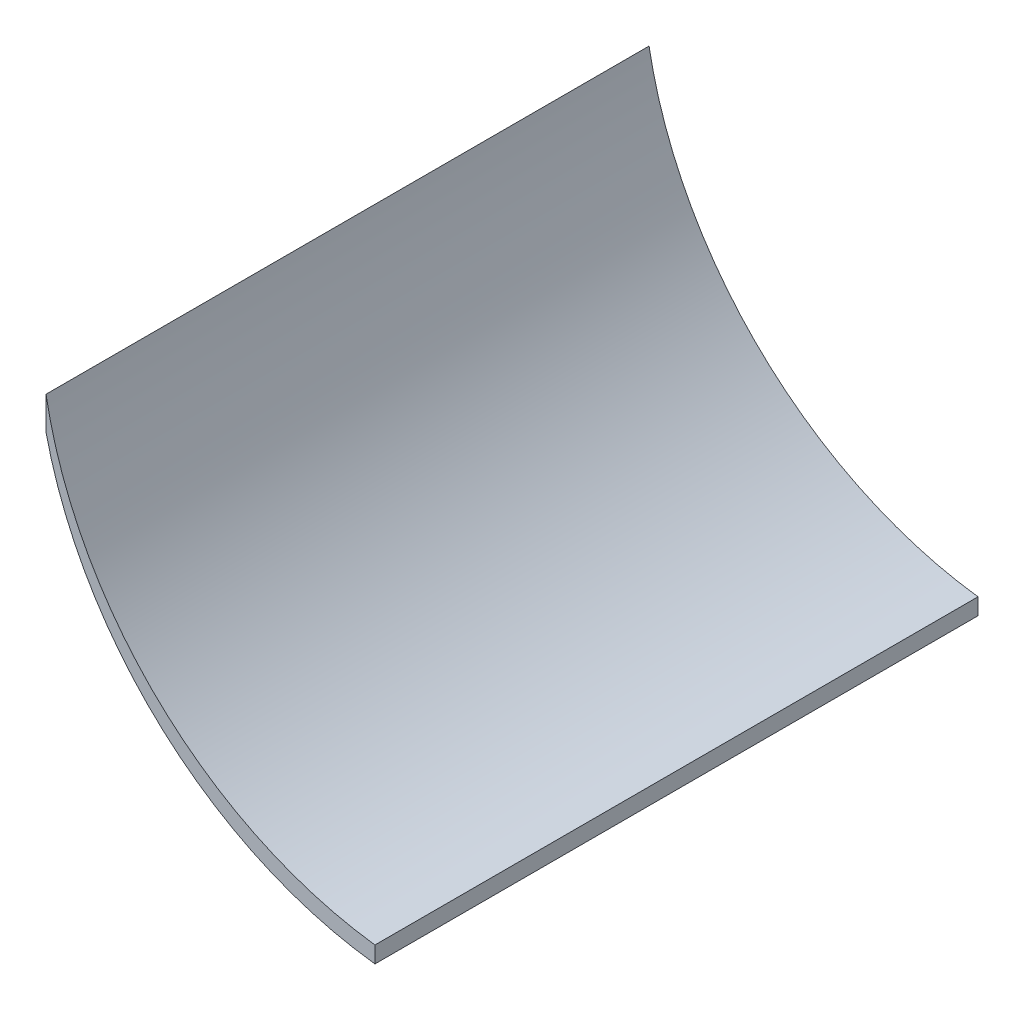
SolidWorks part; units mm, degrees
ref_plane "Front Plane" through (0, 0, 0) normal (0, 0, 1) x (1, 0, 0)
ref_plane "Top Plane" through (0, 0, 0) normal (0, 1, 0) x (1, 0, 0)
ref_plane "Right Plane" through (0, 0, 0) normal (1, 0, 0) x (0, 0, -1)
sketch "Sketch1" plane through (0, 0, 0) normal (0, 0, 1) x (1, 0, 0)
  line L0 (0, 0) -> (0, 7.62)
  line L1 (0, 7.62) -> (0, -68.58) construction
  line L2 (0, -68.58) -> (76.2, -68.58) construction
  line L3 (76.2, -68.58) -> (76.2, -64.77)
  arc A0 (0, 0) -> (76.2, -68.58) centre (86.69, 19.6989) ccw
  arc A1 (0, 7.62) -> (76.2, -64.77) centre (87.4864, 23.4107) ccw
  dimension "D5" = 88.9
  dimension "D6" = 88.9
  dimension "D1" = 7.62
  dimension "D2" = 76.2
  dimension "D3" = 76.2
  dimension "D4" = 3.81
extrude "Boss-Extrude1" add sketch "Sketch1" along normal blind 139.7
